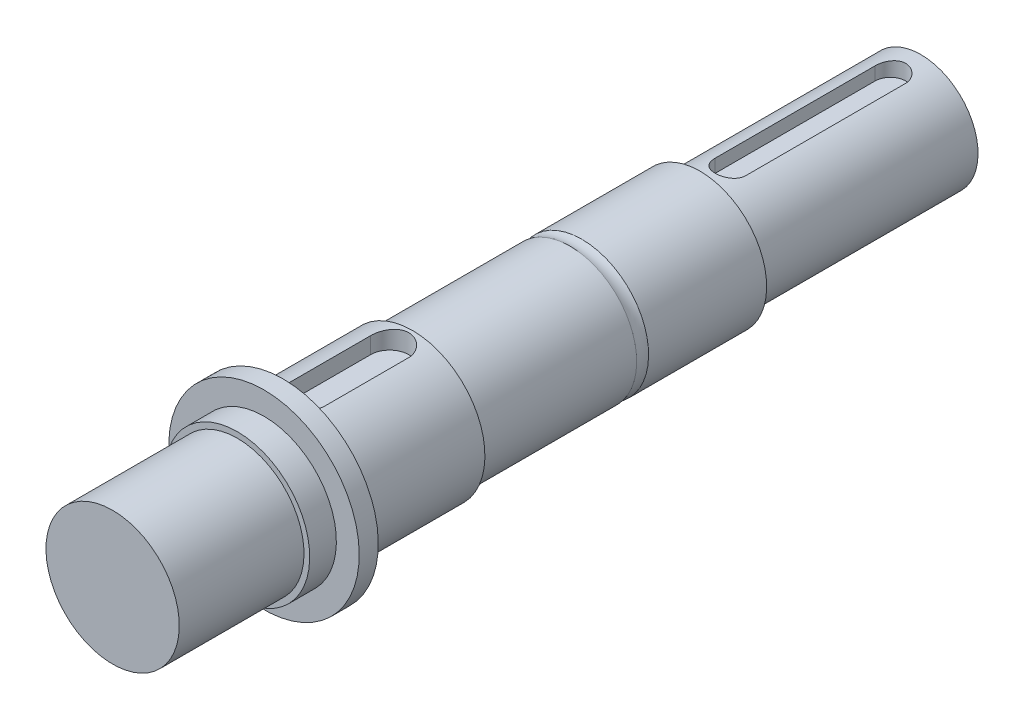
SolidWorks part; units mm, degrees
ref_plane "Front Plane" through (0, 0, 0) normal (0, 0, 1) x (1, 0, 0)
ref_plane "Top Plane" through (0, 0, 0) normal (0, 1, 0) x (1, 0, 0)
ref_plane "Right Plane" through (0, 0, 0) normal (1, 0, 0) x (0, 0, -1)
sketch "Sketch1" plane through (0, 0, 0) normal (1, 0, 0) x (0, 0, -1)
  line L0 (0, 0) -> (0, 15)
  line L1 (0, 15) -> (-58, 15)
  line L2 (-58, 15) -> (-58, 17.5)
  line L3 (-133.4725, 17.5) -> (-133.4725, 19)
  line L4 (-92.1225, 17.5) -> (-133.4725, 17.5)
  line L5 (0, 0) -> (-212.2225, 0)
  line L6 (-58, 17.5) -> (-89, 17.5)
  line L7 (-133.4725, 19) -> (-167.4725, 19)
  line L8 (-167.4725, 19) -> (-167.4725, 25)
  line L9 (-167.4725, 25) -> (-172.4725, 25)
  line L10 (-172.4725, 25) -> (-172.4725, 19)
  line L11 (-172.4725, 19) -> (-179.4725, 19)
  line L12 (-179.4725, 19) -> (-179.4725, 17.5)
  line L13 (-179.4725, 17.5) -> (-212.2225, 17.5)
  line L14 (-212.2225, 17.5) -> (-212.2225, 0)
  arc A0 (-92.1225, 17.5) -> (-89, 17.5) centre (-90.5612, 22.25) ccw
  point P16 (-90.5612, 17.25)
  dimension "D2" = 5
  dimension "D1" = 0.25
  dimension "D3" = 17.5
  dimension "D4" = 15
  dimension "D5" = 17.5
  dimension "D6" = 58
  dimension "D7" = 31
  dimension "D8" = 41.35
  dimension "D9" = 19
  dimension "D10" = 34
  dimension "D11" = 25
  dimension "D12" = 5
  dimension "D13" = 7
  dimension "D14" = 17.5
  dimension "D15" = 32.75
revolve "Revolve1" add sketch "Sketch1" angle 360 about L5
ref_plane "Plane1" through (0, 14, 0) normal (0, 1, 0) x (1, 0, 0)
sketch "Sketch2" plane through (0, 14, 0) normal (0, 1, 0) x (1, 0, 0)
  line L0 (0, -139.4725) -> (0, -161.4725) construction
  line L1 (5, -139.4725) -> (5, -161.4725)
  line L2 (-5, -139.4725) -> (-5, -161.4725)
  line L3 (-19, -133.4725) -> (-19, -167.4725) construction
  line L4 (25, -167.4725) -> (-25, -167.4725) construction
  arc A0 (5, -139.4725) -> (-5, -139.4725) centre (0, -139.4725) ccw
  arc A1 (-5, -161.4725) -> (5, -161.4725) centre (0, -161.4725) ccw
  point P2 (0, -150.4725)
  point P13 (-19, -150.4725)
  dimension "D1" = 10
  dimension "D2" = 22
extrude "Cut-Extrude1" cut sketch "Sketch2" along normal up to next
ref_plane "Plane2" through (0, 11, 0) normal (0, 1, 0) x (1, 0, 0)
sketch "Sketch3" plane through (0, 11, 0) normal (0, 1, 0) x (1, 0, 0)
  line L0 (0, -50) -> (0, -8) construction
  line L1 (-4, -50) -> (-4, -8)
  line L2 (4, -50) -> (4, -8)
  line L3 (-15, 0) -> (-15, -58) construction
  arc A0 (-4, -50) -> (4, -50) centre (0, -50) ccw
  arc A1 (4, -8) -> (-4, -8) centre (0, -8) ccw
  point P2 (0, -29)
  point P8 (-15, -29)
  dimension "D1" = 8
  dimension "D2" = 42
extrude "Cut-Extrude2" cut sketch "Sketch3" along normal up to next
